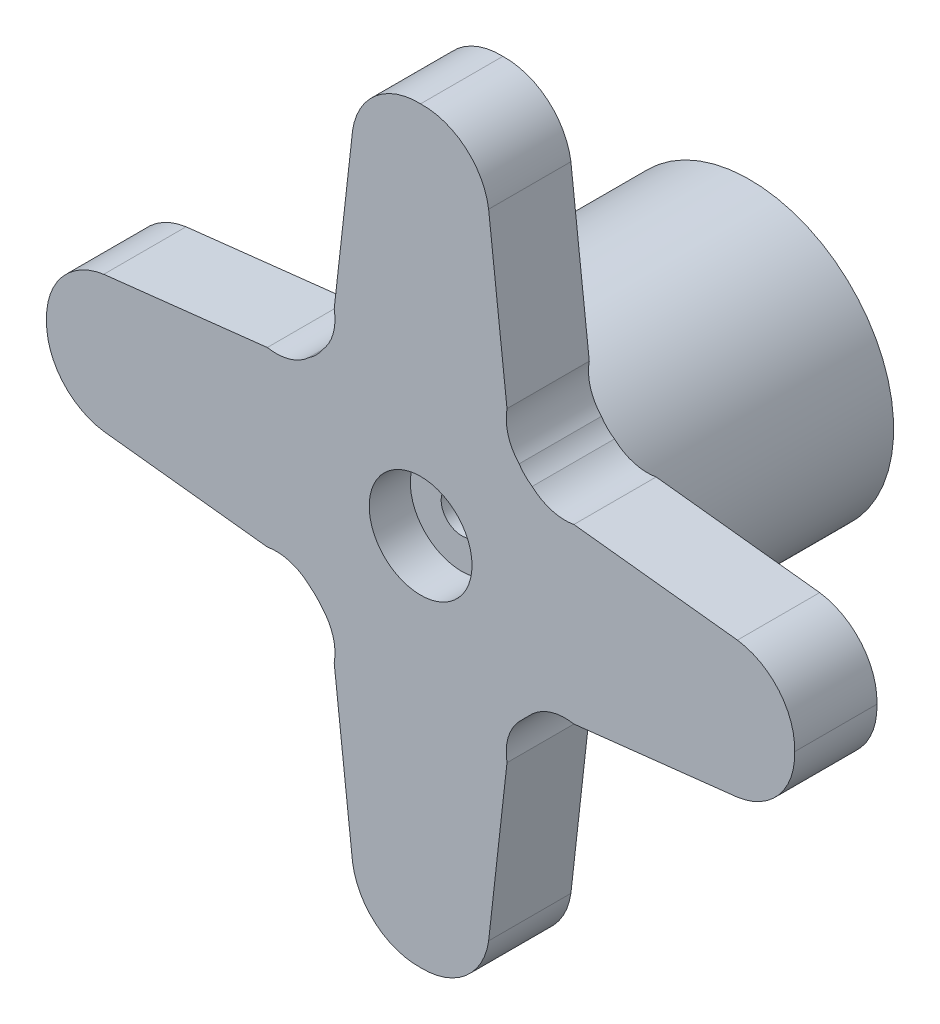
SolidWorks part; units mm, degrees
ref_plane "Front Plane" through (0, 0, 0) normal (0, 0, 1) x (1, 0, 0)
ref_plane "Top Plane" through (0, 0, 0) normal (0, 1, 0) x (1, 0, 0)
ref_plane "Right Plane" through (0, 0, 0) normal (1, 0, 0) x (0, 0, -1)
sketch "Sketch1" plane through (0, 0, 0) normal (0, 0, 1) x (1, 0, 0)
  line L0 (0, 9.0929) -> (0, -9.0929) construction
  line L1 (-14.2436, 0) -> (14.2436, 0) construction
  line L2 (3.5535, -3.5535) -> (14.7335, -14.7335) construction
  line L3 (1.6538, -7.7014) -> (2.1003, -3.7264)
  line L4 (7.7014, -1.6538) -> (3.7264, -2.1003)
  line L5 (7.7014, 1.6538) -> (3.7264, 2.1003)
  line L6 (1.6538, 7.7014) -> (2.1003, 3.7264)
  line L7 (-3.5535, -3.5535) -> (-14.7335, -14.7335) construction
  line L8 (-1.6538, 7.7014) -> (-2.1003, 3.7264)
  line L9 (-7.7014, 1.6538) -> (-3.7264, 2.1003)
  line L10 (-7.7014, -1.6538) -> (-3.7264, -2.1003)
  line L11 (-1.6538, -7.7014) -> (-2.1003, -3.7264)
  arc A0 (0, -9.0929) -> (1.6538, -7.7014) centre (0.0512, -7.4752) ccw
  arc A1 (2.1003, -3.7264) -> (2.3952, -2.7127) centre (3.2543, -3.5124) cw
  arc A2 (9.0929, 0) -> (7.7014, -1.6538) centre (7.4752, -0.0512) cw
  arc A3 (3.7264, -2.1003) -> (2.7127, -2.3952) centre (3.5124, -3.2543) ccw
  arc A4 (3.7264, 2.1003) -> (2.7127, 2.3952) centre (3.5124, 3.2543) cw
  arc A5 (9.0929, 0) -> (7.7014, 1.6538) centre (7.4752, 0.0512) ccw
  arc A6 (2.1003, 3.7264) -> (2.3952, 2.7127) centre (3.2543, 3.5124) ccw
  arc A7 (0, 9.0929) -> (1.6538, 7.7014) centre (0.0512, 7.4752) cw
  arc A8 (0, 9.0929) -> (-1.6538, 7.7014) centre (-0.0512, 7.4752) ccw
  arc A9 (-2.1003, 3.7264) -> (-2.3952, 2.7127) centre (-3.2543, 3.5124) cw
  arc A10 (-9.0929, 0) -> (-7.7014, 1.6538) centre (-7.4752, 0.0512) cw
  arc A11 (-3.7264, 2.1003) -> (-2.7127, 2.3952) centre (-3.5124, 3.2543) ccw
  arc A12 (-3.7264, -2.1003) -> (-2.7127, -2.3952) centre (-3.5124, -3.2543) cw
  arc A13 (-9.0929, 0) -> (-7.7014, -1.6538) centre (-7.4752, -0.0512) ccw
  arc A14 (-2.1003, -3.7264) -> (-2.3952, -2.7127) centre (-3.2543, -3.5124) ccw
  arc A15 (0, -9.0929) -> (-1.6538, -7.7014) centre (-0.0512, -7.4752) cw
  arc A16 (-2.7127, 2.3952) -> (-2.3952, 2.7127) centre (-3.3106, 3.3106) ccw
  arc A17 (2.7127, 2.3952) -> (2.3952, 2.7127) centre (3.3106, 3.3106) cw
  arc A18 (-2.7127, -2.3952) -> (-2.3952, -2.7127) centre (-3.6412, -3.6412) cw
  arc A19 (2.7127, -2.3952) -> (2.3952, -2.7127) centre (303.6769, -303.6769) ccw
  point P4 (0, 0)
  point P7 (0, 0)
extrude "Boss-Extrude1" add sketch "Sketch1" along normal blind 2
sketch "Sketch2" plane through (0, 0, 0) normal (0, 0, -1) x (-1, 0, 0)
  circle A0 centre (0, 0) radius 3.5
  circle A1 centre (0, 0) radius 2.5
  dimension "D1" = 7
  dimension "D2" = 5
extrude "Boss-Extrude2" add sketch "Sketch2" along normal blind 6
sketch "Sketch3" plane through (0, 0, 2) normal (0, 0, 1) x (1, 0, 0)
  circle A0 centre (0, 0) radius 1.25
  dimension "D1" = 2.5
extrude "Cut-Extrude1" cut sketch "Sketch3" against normal blind 1
sketch "Sketch4" plane through (0, 0, 1) normal (0, 0, 1) x (1, 0, 0)
  circle A0 centre (0, 0) radius 0.5
  dimension "D1" = 1
extrude "Cut-Extrude2" cut sketch "Sketch4" against normal blind 1
